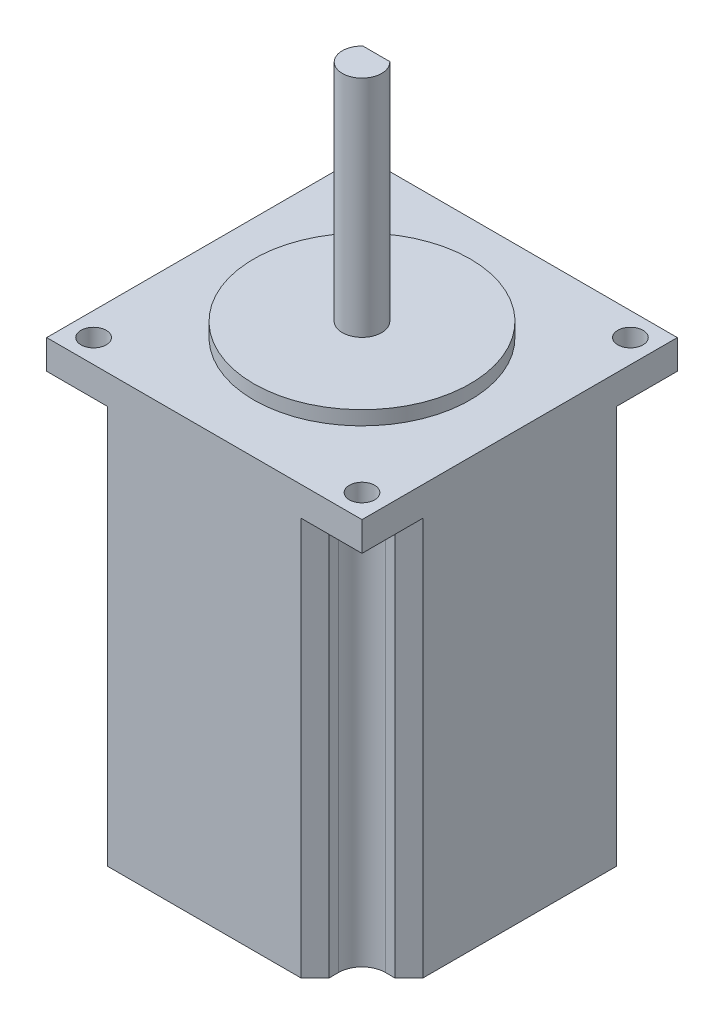
SolidWorks part; units mm, degrees
ref_plane "Alzado" through (0, 0, 0) normal (0, 0, 1) x (1, 0, 0)
ref_plane "Planta" through (0, 0, 0) normal (0, 1, 0) x (1, 0, 0)
ref_plane "Vista lateral" through (0, 0, 0) normal (1, 0, 0) x (0, 0, -1)
sketch "Croquis1" plane through (0, 0, 0) normal (0, 1, 0) x (1, 0, 0)
  line L1 (28.05, 28.05) -> (-28.05, 28.05)
  line L2 (28.05, 28.05) -> (28.05, -28.05)
  line L3 (28.05, -28.05) -> (-28.05, -28.05)
  line L4 (-28.05, 28.05) -> (-28.05, -28.05)
  line L5 (28.05, 28.05) -> (-28.05, -28.05) construction
  line L6 (28.05, -28.05) -> (-28.05, 28.05) construction
  point P0 (0, 0)
  dimension "D1" = 56.1
extrude "Saliente-Extruir1" add sketch "Croquis1" along normal blind 76.05
ref_plane "Plano1" through (0, 70.85, 0) normal (0, 1, 0) x (1, 0, 0)
sketch "Croquis2" plane through (0, 70.85, 0) normal (0, 1, 0) x (1, 0, 0)
  line L0 (-28.05, 19.7) -> (-23.875, 19.7)
  line L3 (-28.05, 28.05) -> (-28.05, -28.05) construction
  line L4 (-19.7, 23.875) -> (-19.7, 28.05)
  line L6 (28.05, 28.05) -> (-28.05, 28.05) construction
  line L7 (-28.05, 19.7) -> (-28.05, 28.05)
  line L8 (-28.05, 28.05) -> (-19.7, 28.05)
  arc A0 (-23.875, 19.7) -> (-19.7, 23.875) centre (-23.875, 23.875) ccw
  point P11 (-28.05, 23.875)
  dimension "D1" = 8.35
extrude "Cortar-Extruir1" cut sketch "Croquis2" against normal through all
mirror "Simetría3" about plane through (0, 0, 0) normal (1, 0, 0) of "Cortar-Extruir1" second plane through (0, 0, 0) second plane normal (0, 0, 1)
chamfer "Chaflán1" distance 2.5 angle 45 8 edges at (-28.05, 35.425, -19.7) (-19.7, 35.425, -28.05) (-28.05, 35.425, 19.7) (-19.7, 35.425, 28.05) (28.05, 35.425, -19.7) (19.7, 35.425, -28.05) (28.05, 35.425, 19.7) (19.7, 35.425, 28.05)
sketch "Croquis3" plane through (0, 70.85, 0) normal (0, -1, 0) x (1, 0, 0)
  circle A1 centre (23.875, -23.875) radius 2.25
  arc A2 (23.875, -19.7) -> (19.7, -23.875) centre (23.875, -23.875) ccw construction
  dimension "D1" = 4.5
extrude "Cortar-Extruir2" cut sketch "Croquis3" against normal through all
mirror "Simetría4" about plane through (0, 0, 0) normal (1, 0, 0) of "Cortar-Extruir2" second plane through (0, 0, 0) second plane normal (0, 0, 1)
sketch "Croquis4" plane through (0, 76.05, 0) normal (0, 1, 0) x (1, 0, 0)
  circle A0 centre (0, 0) radius 19.25
  dimension "D1" = 38.5
extrude "Saliente-Extruir2" add sketch "Croquis4" along normal blind 2.5
sketch "Croquis6" plane through (0, 78.55, 0) normal (0, 1, 0) x (1, 0, 0)
  circle A0 centre (0, 0) radius 3.5
  dimension "D1" = 7
extrude "Saliente-Extruir4" add sketch "Croquis6" along normal blind 11.7 contours A0
sketch "Croquis7" plane through (0, 90.25, 0) normal (0, 1, 0) x (1, 0, 0)
  line L0 (-2.3974, 2.55) -> (2.3974, 2.55)
  line L1 (0, -3.5) -> (0, 2.55) construction
  circle A0 centre (0, 0) radius 3.5 construction
  circle A1 centre (0, 0) radius 3.5
  arc A2 (-2.3974, 2.55) -> (2.3974, 2.55) centre (0, 0) ccw
  dimension "D2" = 6.05
  dimension "D1" = 0
extrude "Saliente-Extruir5" add sketch "Croquis7" along normal blind 28.15
sketch "Croquis5" plane through (0, 78.55, 0) normal (0, 1, 0) x (1, 0, 0)
  line L0 (-2.3974, 2.55) -> (2.3974, 2.55)
  line L1 (0, 3.5) -> (0, -3.5) construction
  arc A0 (-2.3974, 2.55) -> (2.3974, 2.55) centre (0, 0) ccw
  dimension "D1" = 7
  dimension "D2" = 6.05
extrude "Saliente-Extruir3" add sketch "Croquis5" along normal blind 39.95
sketch "Croquis8" plane through (0, 118.5, 0) normal (0, 1, 0) x (1, 0, 0)
  point P0 (0, 0)
